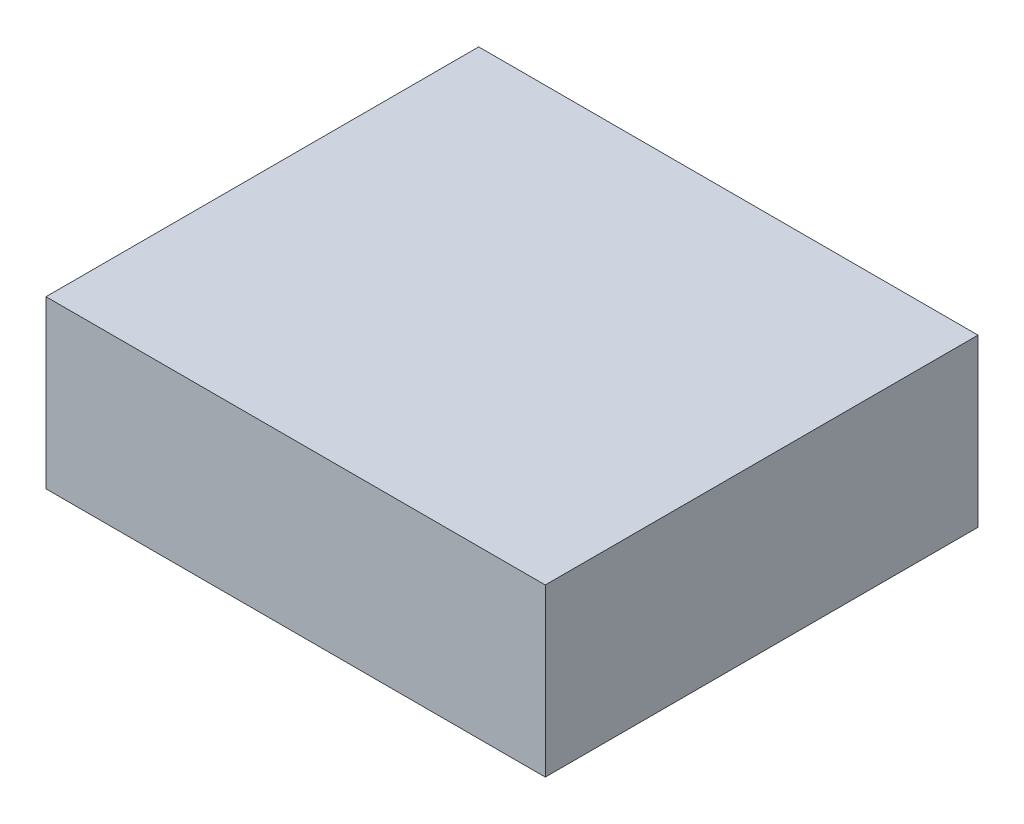
SolidWorks part; units mm, degrees
ref_plane "Front Plane" through (0, 0, 0) normal (0, 0, 1) x (1, 0, 0)
ref_plane "Top Plane" through (0, 0, 0) normal (0, 1, 0) x (1, 0, 0)
ref_plane "Right Plane" through (0, 0, 0) normal (1, 0, 0) x (0, 0, -1)
sketch "Sketch1" plane through (0, 0, 0) normal (0, 1, 0) x (1, 0, 0)
  line L1 (-30, -26) -> (30, -26)
  line L2 (-30, -26) -> (-30, 26)
  line L3 (-30, 26) -> (30, 26)
  line L4 (30, -26) -> (30, 26)
  line L5 (-30, -26) -> (30, 26) construction
  line L6 (-30, 26) -> (30, -26) construction
  point P0 (0, 0)
  dimension "D1" = 60
  dimension "D2" = 52
extrude "Boss-Extrude1" add sketch "Sketch1" along normal blind 20
